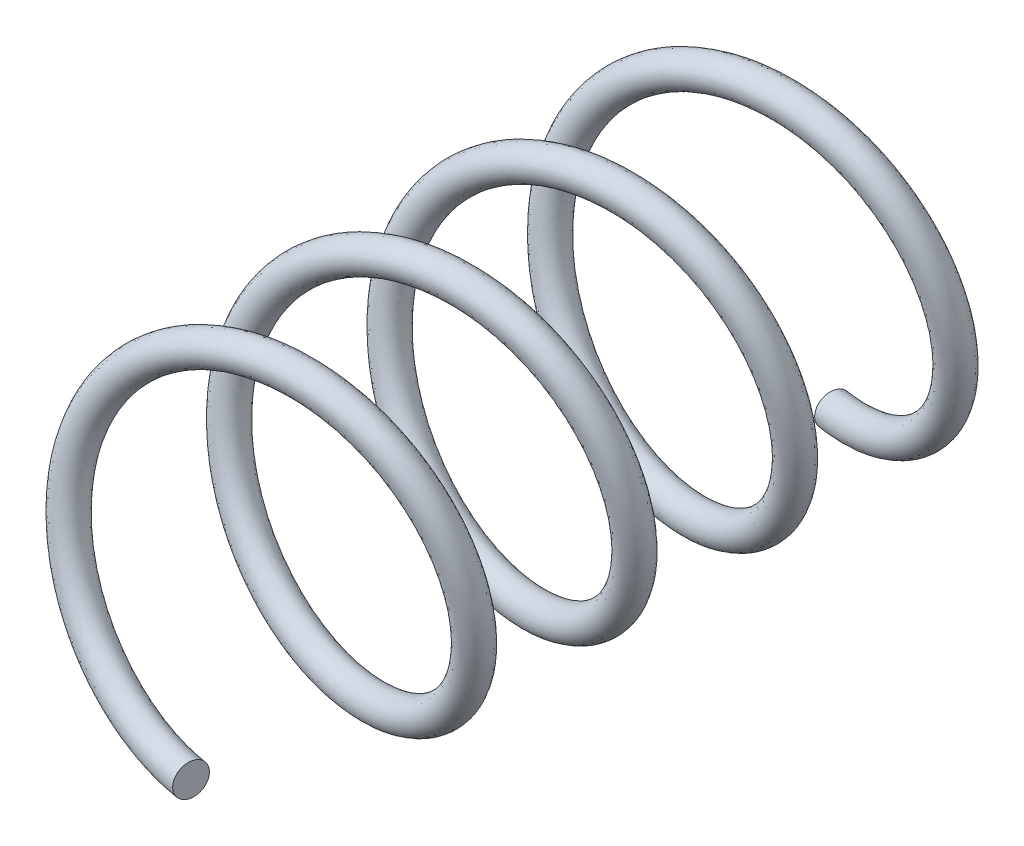
SolidWorks part; units mm, degrees
ref_plane "Alzado" through (0, 0, 0) normal (0, 0, 1) x (1, 0, 0)
ref_plane "Planta" through (0, 0, 0) normal (0, 1, 0) x (1, 0, 0)
ref_plane "Vista lateral" through (0, 0, 0) normal (1, 0, 0) x (0, 0, -1)
sketch "Croquis1" plane through (0, 0, 0) normal (0, 0, 1) x (1, 0, 0)
  circle A0 centre (0, 0) radius 10
  dimension "D1" = 20
curve "Hélice/Espiral1" pitch 10 height 40 turns 4
ref_plane "Plano1" through (0, 0, -40) normal (0, 0, 1) x (1, 0, 0)
sweep "Barrer1" add path "Hélice/Espiral1" circular profile diameter 2 parameters "D3"=2
sketch "Croquis2" plane through (0, 0, 0) normal (0, 1, 0) x (1, 0, 0)
  line L0 (0, 0) -> (0, 55.957) construction
